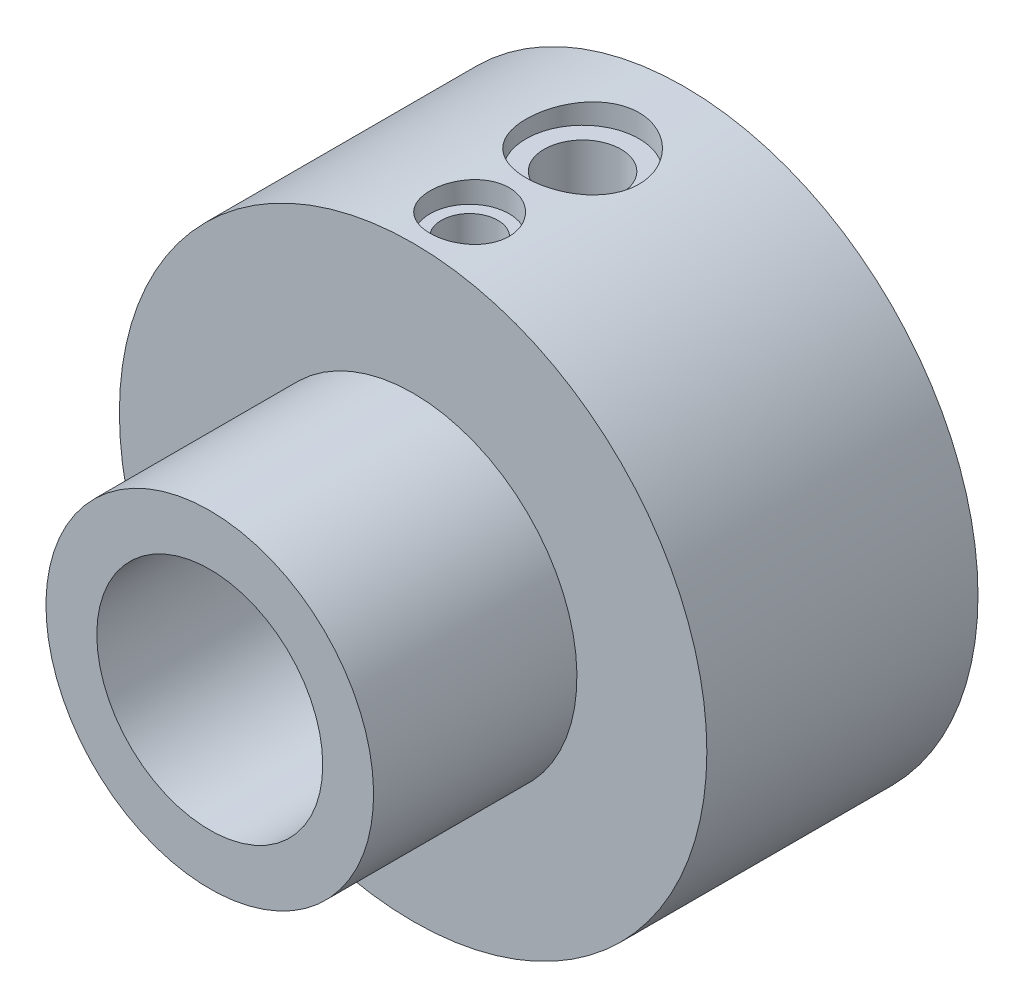
SolidWorks part; units mm, degrees
ref_plane "Front Plane" through (0, 0, 0) normal (0, 0, 1) x (1, 0, 0)
ref_plane "Top Plane" through (0, 0, 0) normal (0, 1, 0) x (1, 0, 0)
ref_plane "Right Plane" through (0, 0, 0) normal (1, 0, 0) x (0, 0, -1)
sketch "Sketch1" plane through (0, 0, 0) normal (1, 0, 0) x (0, 0, -1)
  line L0 (0, 0) -> (0, 14.5)
  line L1 (0, 14.5) -> (18, 14.5)
  line L2 (18, 14.5) -> (18, 26)
  line L3 (18, 26) -> (42, 26)
  line L4 (42, 26) -> (42, 0)
  line L5 (42, 0) -> (0, 0)
  dimension "D1" = 14.5
  dimension "D2" = 26
  dimension "D3" = 42
  dimension "D4" = 24
revolve "Revolve1" add sketch "Sketch1" angle 360 about L5
sketch "Sketch2" plane through (0, 0, 0) normal (0, 0, 1) x (1, 0, 0)
  circle A0 centre (0, 0) radius 10
  dimension "D1" = 20
extrude "Cut-Extrude1" cut sketch "Sketch2" against normal through all
sketch "Sketch3" plane through (0, 0, 0) normal (0, 1, 0) x (1, 0, 0)
  line L0 (-14.5, 18) -> (14.5, 18) construction
  circle A0 centre (0, 33) radius 5
  circle A1 centre (0, 23) radius 3.5
  dimension "D1" = 10
  dimension "D2" = 7
  dimension "D3" = 15
  dimension "D4" = 5
extrude "Cut-Extrude2" cut sketch "Sketch3" along normal up to next from offset 24
hole_wizard "M8x1.25 Tapped Hole1" positions "Sketch4" profile "Sketch5" tap size "M8x1.25" standard "ANSI Metric"
sketch "Sketch4" plane through (0, 24, 0) normal (0, 1, 0) x (1, 0, 0)
  circle A0 centre (0, 33) radius 5 construction
  point P0 (0, 33)
  point P4 (0, 0)
  point P5 (-0.5495, 32.6609)
  point P6 (0, 0)
sketch "Sketch5" plane through (0, 24, -33) normal (1, 0, 0) x (0, 0, 1)
  line L0 (0, 0) -> (0, 14)
  line L1 (0, 14) -> (3.4, 14)
  line L2 (3.4, 14) -> (3.4, 0)
  line L5 (3.4, 0) -> (0, 0)
  line L11 (0, -6.35) -> (0, 107.95) construction
  dimension "Thru Tap Drill Dia." = 6.8
  dimension "Thru Tap Drill Depth" = 14
cosmetic thread "Hole Thread1" parameters "D2"=8
hole_wizard "Ø5.0 (5) Diameter Hole1" positions "Sketch8" profile "Sketch9" hole size "Ø5.0" standard "ANSI Metric" end condition through all
sketch "Sketch8" plane through (0, 24, 0) normal (0, 1, 0) x (1, 0, 0)
  circle A0 centre (0, 23) radius 3.5 construction
  point P0 (0, 23)
sketch "Sketch9" plane through (0, 24, -23) normal (1, 0, 0) x (0, 0, 1)
  line L0 (0, 0) -> (0, 50)
  line L1 (0, 50) -> (2.5, 50)
  line L2 (2.5, 50) -> (2.5, 0)
  line L5 (2.5, 0) -> (0, 0)
  line L11 (0, -6.35) -> (0, 107.95) construction
  dimension "Thru Hole Dia." = 5
  dimension "Thru Hole Depth" = 50
